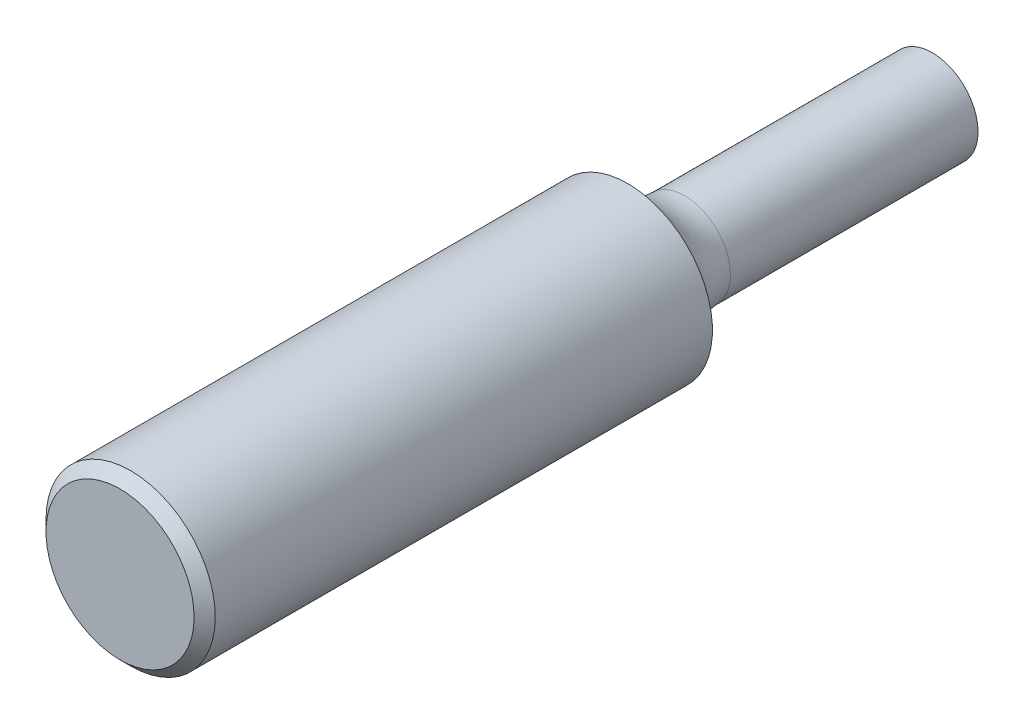
SolidWorks part; units mm, degrees
material "O1 Steel"
ref_plane "Alzado" through (0, 0, 0) normal (0, 0, 1) x (1, 0, 0)
ref_plane "Planta" through (0, 0, 0) normal (0, 1, 0) x (1, 0, 0)
ref_plane "Vista lateral" through (0, 0, 0) normal (1, 0, 0) x (0, 0, -1)
sketch "Croquis1" plane through (0, 0, 0) normal (1, 0, 0) x (0, 0, -1)
  line L0 (127, 0) -> (-127, 0) construction
  line L1 (-15.24, 0) -> (-15.24, 3.175)
  line L2 (-15.24, 3.175) -> (3.81, 3.175)
  line L4 (5.9417, 1.7145) -> (15.24, 1.7145)
  line L5 (15.24, 1.7145) -> (15.24, 0)
  line L6 (15.24, 0) -> (-15.24, 0)
  arc A0 (3.81, 3.175) -> (5.9417, 1.7145) centre (5.9417, 4.0005) ccw
  dimension "D6" = 2.286
  dimension "D1" = 254
  dimension "D2" = 6.35
  dimension "D3" = 30.48
  dimension "D4" = 19.05
  dimension "D5" = 3.429
revolve "Revolución1" add sketch "Croquis1" angle 360 about L0
sketch "Croquis4" plane through (0, 0, 0) normal (1, 0, 0) x (0, 0, -1)
  line L0 (15.24, 0) -> (-15.24, 0) construction
  line L1 (15.24, -1.7145) -> (15.24, 1.7145) construction
  line L2 (-15.24, 3.175) -> (-15.24, -3.175) construction
  line L4 (14.732, 0) -> (15.24, 0)
  line L5 (15.24, 0) -> (15.24, 1.7227)
  arc A1 (14.732, 0) -> (15.24, 1.7227) centre (17.907, 0) cw
  dimension "D1" = 3.175
  dimension "D2" = 0.508
revolve "Cortar-Revolución1" cut sketch "Croquis4" angle 360 about L0
chamfer "Chaflán1" distance 0.3969 angle 45 1 edges at (-3.175, 0, 15.24)
